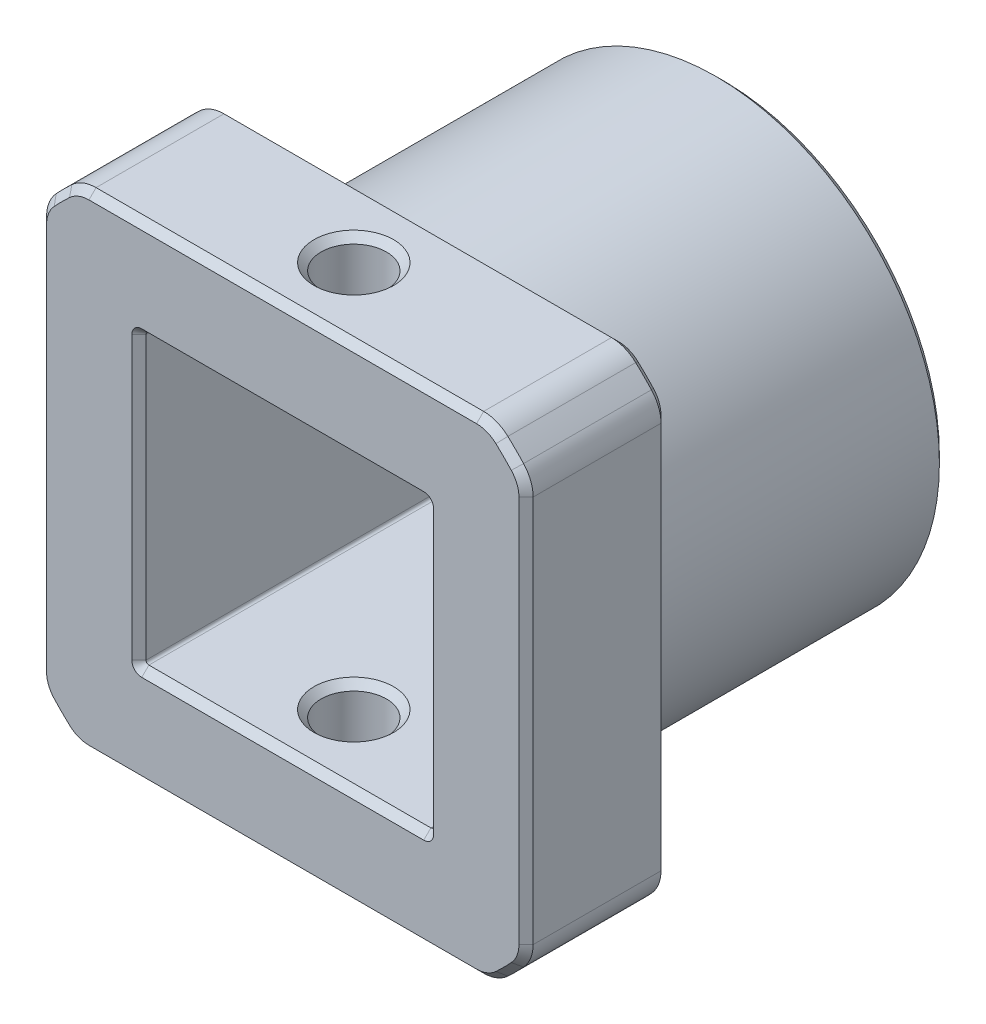
SolidWorks part; units mm, degrees
ref_plane "Front" through (0, 0, 0) normal (0, 0, 1) x (1, 0, 0)
ref_plane "Top" through (0, 0, 0) normal (0, 1, 0) x (1, 0, 0)
ref_plane "Right" through (0, 0, 0) normal (1, 0, 0) x (0, 0, -1)
sketch "Skizze1" plane through (0, 0, 0) normal (0, 0, 1) x (1, 0, 0)
  line L1 (-10.125, -10.125) -> (10.125, -10.125)
  line L2 (-10.125, -10.125) -> (-10.125, 10.125)
  line L3 (-10.125, 10.125) -> (10.125, 10.125)
  line L4 (10.125, -10.125) -> (10.125, 10.125)
  line L5 (-10.125, -10.125) -> (10.125, 10.125) construction
  line L6 (-10.125, 10.125) -> (10.125, -10.125) construction
  circle A0 centre (0, 0) radius 15.725
  point P0 (0, 0)
  dimension "D2" = 31.45
  dimension "D1" = 20.25
extrude "Aufsatz-Linear austragen1" add sketch "Skizze1" along normal blind 21
sketch "Skizze2" plane through (0, 0, 21) normal (0, 0, 1) x (1, 0, 0)
  line L0 (-14.594, 17.125) -> (14.594, 17.125)
  line L1 (-10.125, -10.125) -> (10.125, -10.125)
  line L2 (-10.125, -10.125) -> (-10.125, 10.125)
  line L3 (-10.125, 10.125) -> (10.125, 10.125)
  line L4 (10.125, -10.125) -> (10.125, 10.125)
  line L5 (-10.125, -10.125) -> (10.125, 10.125) construction
  line L6 (-10.125, 10.125) -> (10.125, -10.125) construction
  line L7 (0, 0) -> (13.8508, 0) construction
  line L8 (0, 0) -> (0, 13.2524) construction
  line L9 (17.125, -14.594) -> (17.125, 14.594)
  line L10 (14.594, -17.125) -> (-14.594, -17.125)
  line L11 (-17.125, 14.594) -> (-17.125, -14.594)
  arc A0 (-14.594, 17.125) -> (-17.125, 14.594) centre (0, 0) ccw
  arc A2 (-17.125, -14.594) -> (-14.594, -17.125) centre (0, 0) ccw
  arc A3 (14.594, -17.125) -> (17.125, -14.594) centre (0, 0) ccw
  arc A4 (17.125, 14.594) -> (14.594, 17.125) centre (0, 0) ccw
  dimension "D1" = 45
  dimension "D2" = 7
extrude "Aufsatz-Linear austragen2" add sketch "Skizze2" along normal blind 10
sketch "Skizze3" plane through (0, 17.125, 0) normal (0, 1, 0) x (1, 0, 0)
  line L0 (0, -21) -> (0, -31) construction
  line L2 (14.594, -31) -> (-14.594, -31) construction
  circle A0 centre (0, -26) radius 2.3
  dimension "D1" = 4.6
  dimension "D2" = 10
extrude "Schnitt-Linear austragen1" cut sketch "Skizze3" against normal through all
pattern_circular "Kreismuster1" [suppressed] count 2 over 90
fillet "Verrundung1" radius 0.2 4 edges at (10.125, -10.125, 15.5) (-10.125, -10.125, 15.5) (-10.125, 10.125, 15.5) (10.125, 10.125, 15.5)
fillet "Verrundung2" radius 2.5 8 edges at (-17.125, -14.594, 26) (-14.594, -17.125, 26) (14.594, -17.125, 26) (17.125, -14.594, 26) (17.125, 14.594, 26) (14.594, 17.125, 26) (-17.125, 14.594, 26) (-14.594, 17.125, 26)
chamfer "Fase1" distance 0.5 angle 45 37 edges at (-10.0664, -10.0664, 0) (-10.125, 0, 0) (-10.0664, 10.0664, 0) (0, 10.125, 0) (10.0664, 10.0664, 0) (10.125, 0, 0) (10.0664, -10.0664, 0) (0, -10.125, 0) (15.725, 0, 0) (-10.0664, 10.0664, 31) (-10.125, 0, 31) (-10.0664, -10.0664, 31) (0, -10.125, 31) (10.0664, -10.0664, 31) (10.125, 0, 31) (10.0664, 10.0664, 31) (0, 10.125, 31) (-16.951, 14.5586, 31) (-15.9099, 15.9099, 31) (-14.5586, 16.951, 31) (0, 17.125, 31) (14.5586, 16.951, 31) (15.9099, 15.9099, 31) (16.951, 14.5586, 31) (17.125, 0, 31) (16.951, -14.5586, 31) (15.9099, -15.9099, 31) (14.5586, -16.951, 31) (0, -17.125, 31) (-14.5586, -16.951, 31) (-15.9099, -15.9099, 31) (-16.951, -14.5586, 31) (-17.125, 0, 31) (0, -10.125, 28.3) (0, 10.125, 23.7) (0, -17.125, 28.3) (0, 17.125, 28.3)
chamfer "Fase2" [suppressed] distance 0.3 angle 45
chamfer "Fase3" [suppressed] distance 0.5 angle 45
chamfer "Fase4" distance 0.5 angle 45 16 edges at (0, -17.125, 21) (14.5586, -16.951, 21) (-14.5586, -16.951, 21) (15.9099, -15.9099, 21) (-15.9099, -15.9099, 21) (16.951, -14.5586, 21) (-16.951, -14.5586, 21) (17.125, 0, 21) (-17.125, 0, 21) (16.951, 14.5586, 21) (-16.951, 14.5586, 21) (15.9099, 15.9099, 21) (-15.9099, 15.9099, 21) (14.5586, 16.951, 21) (-14.5586, 16.951, 21) (0, 17.125, 21)
